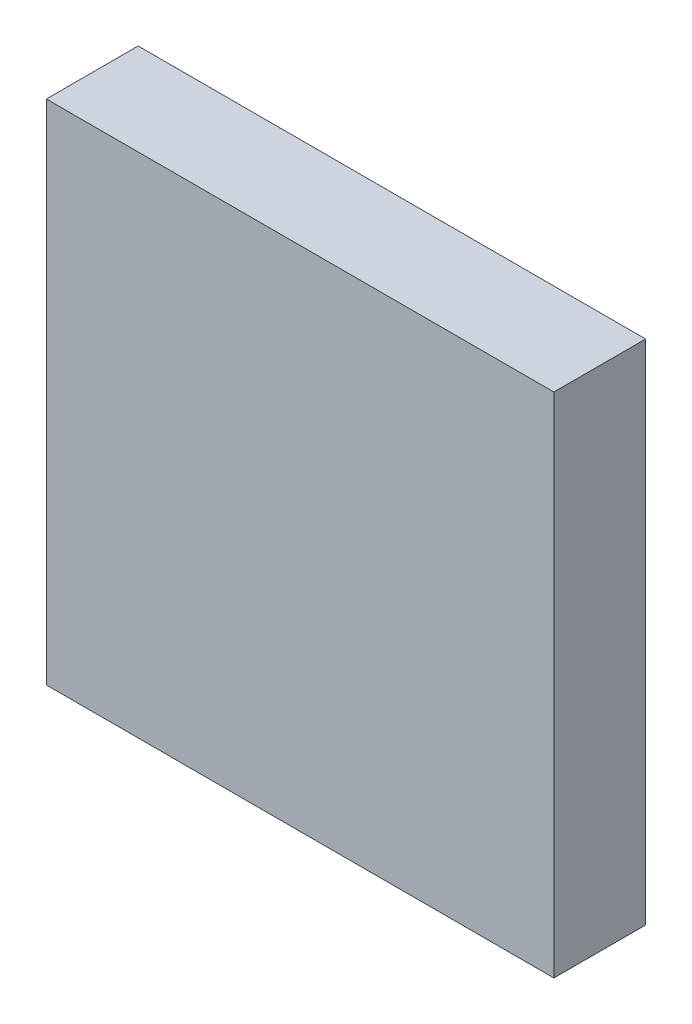
SolidWorks part; units mm, degrees
ref_plane "Plan de face" through (0, 0, 0) normal (0, 0, 1) x (1, 0, 0)
ref_plane "Plan de dessus" through (0, 0, 0) normal (0, 1, 0) x (1, 0, 0)
ref_plane "Plan de droite" through (0, 0, 0) normal (1, 0, 0) x (0, 0, -1)
sketch "Esquisse1" plane through (0, 0, 0) normal (0, 0, 1) x (1, 0, 0)
  line L0 (-2.9032, 2.9032) -> (2.627, 2.9032)
  line L1 (2.627, 2.9032) -> (2.627, -2.627)
  line L2 (2.627, -2.627) -> (-2.9032, -2.627)
  line L3 (-2.9032, -2.627) -> (-2.9032, 2.9032)
extrude "Component_Outline" add sketch "Esquisse1" along normal blind 1 separate body
sketch3d "Esquisse3D1"
  line L0 (0, 0, 0) -> (1, 0, 0)
  line L1 (0, 0, 0) -> (0, 1, 0)
  line L2 (0, 0, 0) -> (0, 0, 1)
  point P0 (0, 0, 0)
